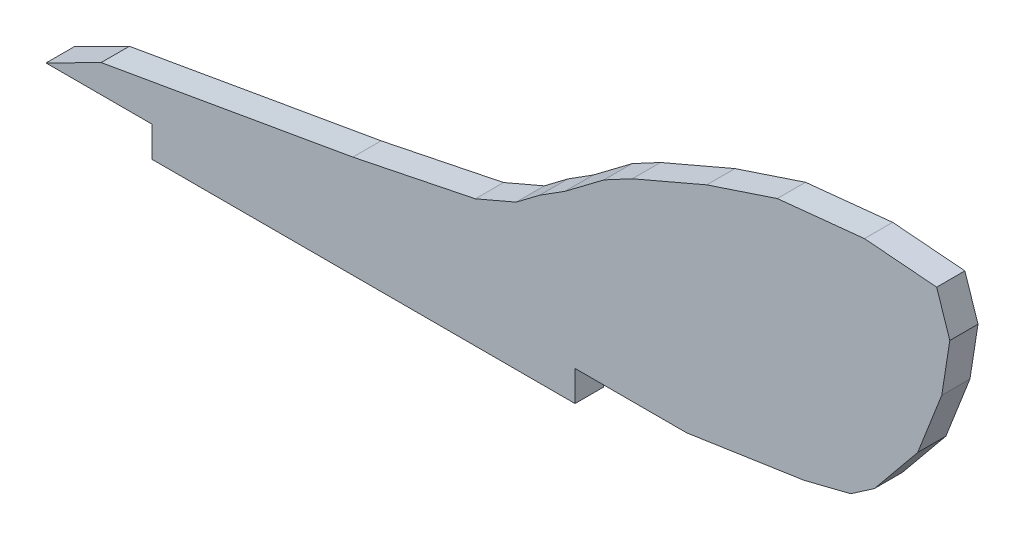
SolidWorks part; units mm, degrees
ref_plane "Front Plane" through (0, 0, 0) normal (0, 0, 1) x (1, 0, 0)
ref_plane "Top Plane" through (0, 0, 0) normal (0, 1, 0) x (1, 0, 0)
ref_plane "Right Plane" through (0, 0, 0) normal (1, 0, 0) x (0, 0, -1)
sketch "Sketch1" plane through (0, 0, 0) normal (0, 0, 1) x (1, 0, 0)
  line L0 (0, 0) -> (9.9314, 5.0292)
  line L1 (9.9314, 5.0292) -> (55.2704, 12.954)
  line L2 (55.2704, 12.954) -> (77.3176, 17.4752)
  line L3 (77.3176, 17.4752) -> (84.6582, 20.6248)
  line L4 (84.6582, 20.6248) -> (88.9, 23.8252)
  line L5 (88.9, 23.8252) -> (93.472, 26.7208)
  line L6 (93.472, 26.7208) -> (100.4824, 32.004)
  line L7 (100.4824, 32.004) -> (105.5907, 34.7345)
  line L8 (105.5907, 34.7345) -> (118.999, 40.4876)
  line L9 (118.999, 40.4876) -> (131.699, 44.704)
  line L10 (131.699, 44.704) -> (147.3962, 46.3042)
  line L11 (147.3962, 46.3042) -> (160.401, 45.2374)
  line L12 (160.401, 45.2374) -> (162.7632, 38.1)
  line L13 (162.7632, 38.1) -> (161.3154, 28.829)
  line L14 (161.3154, 28.829) -> (156.972, 17.7292)
  line L15 (156.972, 17.7292) -> (149.1742, 8.2042)
  line L16 (149.1742, 8.2042) -> (144.9324, 5.2832)
  line L17 (144.9324, 5.2832) -> (136.5504, 3.175)
  line L18 (136.5504, 3.175) -> (115.3922, 0)
  line L19 (0, 0) -> (19.0754, 0)
  line L20 (19.0754, 0) -> (19.0754, -5.4864)
  line L21 (19.0754, -5.4864) -> (95.2754, -5.4864)
  line L22 (95.2754, -5.4864) -> (95.2754, 0)
  line L23 (95.2754, 0) -> (115.3922, 0)
extrude "Boss-Extrude1" add sketch "Sketch1" along normal blind 5.08
